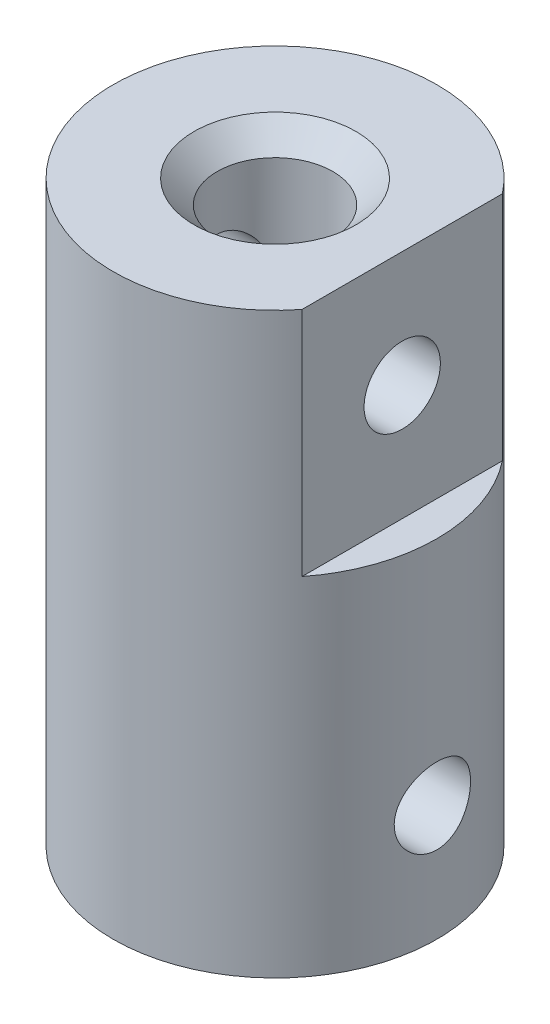
SolidWorks part; units mm, degrees
material "Aluminium"
ref_plane "Front Plane" through (0, 0, 0) normal (0, 0, 1) x (1, 0, 0)
ref_plane "Top Plane" through (0, 0, 0) normal (0, 1, 0) x (1, 0, 0)
ref_plane "Right Plane" through (0, 0, 0) normal (1, 0, 0) x (0, 0, -1)
sketch "Sketch1" plane through (0, 0, 0) normal (0, 0, 1) x (1, 0, 0)
  line L0 (0, 0) -> (0, 17.3335) construction
  line L1 (-2.5, 0) -> (-7, 0)
  line L2 (-2.5, 0) -> (-2.5, 25)
  line L3 (-2.5, 25) -> (-7, 25)
  line L4 (-7, 0) -> (-7, 25)
  dimension "D1" = 5
  dimension "D2" = 14
  dimension "D3" = 25
revolve "Revolve1" add sketch "Sketch1" angle 360 about L0
sketch "Sketch2" plane through (0, 0, 0) normal (0, 0, 1) x (1, 0, 0)
  line L0 (7, 25) -> (-7, 25) construction
  line L1 (5.5, 25) -> (7, 25)
  line L2 (5.5, 25) -> (5.5, 15)
  line L3 (5.5, 15) -> (7, 15)
  line L4 (7, 25) -> (7, 15)
  line L5 (7, 0) -> (7, 25) construction
  line L6 (-7, 25) -> (-7, 0) construction
  dimension "D1" = 10
  dimension "D2" = 12.5
extrude "Cut-Extrude1" cut sketch "Sketch2" against normal through all both and the other way through all
chamfer "Chamfer1" distance 1 angle 45 1 edges at (0, 25, -2.5)
hole_wizard "M8 Tapped Hole1" positions "Sketch4" profile "Sketch3" tap size "M8" standard "DIN"
sketch "Sketch4" plane through (0, 0, 0) normal (0, -1, 0) x (-1, 0, 0)
  point P0 (0, 0)
sketch "Sketch3" plane through (0, 0, 0) normal (1, 0, 0) x (0, 0, -1)
  line L0 (0, 0) -> (0, 18.0429)
  line L1 (0, 18.0429) -> (3.4, 16)
  line L2 (3.4, 16) -> (3.4, 0)
  line L5 (3.4, 0) -> (0, 0)
  line L10 (0, 18.0429) -> (-3.4, 16) construction
  line L11 (0, -6.35) -> (0, 107.95) construction
  dimension "Tap Drill Dia." = 6.8
  dimension "Tap Drill Depth" = 16
  dimension "Drill Angle" = 118
cosmetic thread "Hole Thread1" parameters "D1"=12, "D2"=8
ref_plane "Plane1" through (7, 0, 0) normal (1, 0, 0) x (0, 0, -1)
hole_wizard "M4 Tapped Hole1" positions "Sketch6" profile "Sketch7" tap size "M4" standard "DIN" end condition through all
sketch "Sketch6" plane through (7, 0, 0) normal (1, 0, 0) x (0, 0, -1)
  line L0 (0, 0) -> (0, 5) construction
  line L3 (0, 25) -> (0, 20) construction
  line L4 (4.3301, 25) -> (-4.3301, 25) construction
  point P0 (0, 20)
  point P2 (0, 5)
  dimension "D1" = 5
  dimension "D2" = 5
sketch "Sketch7" plane through (7, 20, 0) normal (0, 1, 0) x (0, 0, -1)
  line L0 (0, 0) -> (0, 14)
  line L1 (0, 14) -> (1.65, 14)
  line L2 (1.65, 14) -> (1.65, 0)
  line L5 (1.65, 0) -> (0, 0)
  line L11 (0, -6.35) -> (0, 107.95) construction
  dimension "Thru Tap Drill Dia." = 3.3
  dimension "Thru Tap Drill Depth" = 14
cosmetic thread "Hole Thread2"
cosmetic thread "Hole Thread3"
